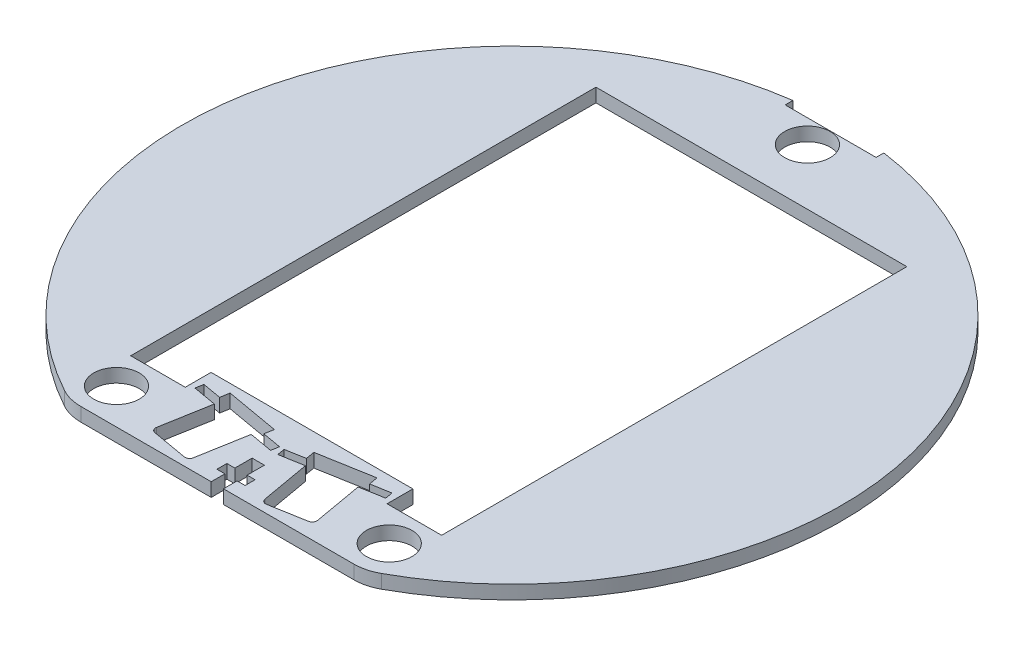
SolidWorks part; units mm, degrees
ref_plane "Front Plane" through (0, 0, 0) normal (0, 0, 1) x (1, 0, 0)
ref_plane "Top Plane" through (0, 0, 0) normal (0, 1, 0) x (1, 0, 0)
ref_plane "Right Plane" through (0, 0, 0) normal (1, 0, 0) x (0, 0, -1)
sketch "Sketch1" plane through (0, 0, 0) normal (0, 1, 0) x (1, 0, 0)
  line L0 (-30.03, -64.8129) -> (30.03, -64.8129)
  line L1 (0, -85) -> (0, 0) construction
  line L2 (0, -85) -> (32.4891, -64.8129) construction
  arc A0 (34.8348, -63.5829) -> (-34.8348, -63.5829) centre (0, 0) ccw
  circle A1 centre (0, -85) radius 38.25 construction
  arc A2 (30.03, -64.8129) -> (34.8348, -63.5829) centre (30.03, -54.8129) ccw
  arc A3 (-30.03, -64.8129) -> (-34.8348, -63.5829) centre (-30.03, -54.8129) cw
  dimension "D1" = 145
  dimension "D2" = 76.5
  dimension "D4" = 10
  dimension "D3" = 85
extrude "Boss-Extrude1" add sketch "Sketch1" along normal blind 3
sketch "Sketch2" plane through (0, 3, 0) normal (0, 1, 0) x (1, 0, 0)
  line L0 (-34.2, -49.6757) -> (-22.2, -49.6757)
  line L1 (-22.2, -49.6757) -> (-22.2, -44)
  line L2 (-22.2, 49.6757) -> (-22.2, 44)
  line L3 (0, 0) -> (0, -44) construction
  line L4 (34.2, 49.6757) -> (22.2, 49.6757)
  line L5 (34.2, -49.6757) -> (34.2, 49.6757)
  line L6 (22.2, 49.6757) -> (22.2, 44)
  line L7 (22.2, -49.6757) -> (22.2, -44)
  line L8 (34.2, -49.6757) -> (22.2, -49.6757)
  line L55 (-22.2, 44) -> (22.2, 44)
  line L63 (-34.2, -49.6757) -> (-34.2, 49.6757)
  line L64 (-34.2, 49.6757) -> (-22.2, 49.6757)
  line L77 (-22.2, -44) -> (22.2, -44)
  point P9 (0, 44)
  dimension "D1" = 44
  dimension "D2" = 44
  dimension "D3" = 34.2
  dimension "D4" = 12
  dimension "D5" = 49.6757
  dimension "D6" = 49.6757
extrude "Cut-Extrude1" cut sketch "Sketch2" against normal through all
sketch "Sketch4" plane through (0, 3, 0) normal (0, 1, 0) x (1, 0, 0)
  line L0 (-20.9838, -48.7531) -> (-0.7952, -52.3129)
  line L1 (20.9838, -48.7531) -> (20.6886, -47.0789)
  line L2 (0.7952, -52.3129) -> (0.5, -50.6387)
  line L3 (20.6886, -47.0789) -> (0.5, -50.6387)
  line L4 (0, 0) -> (0, -64.8129) construction
  line L5 (-30.03, -64.8129) -> (30.03, -64.8129) construction
  line L6 (-20.6886, -47.0789) -> (-0.5, -50.6387)
  line L7 (-0.7952, -52.3129) -> (-0.5, -50.6387)
  line L8 (-20.9838, -48.7531) -> (-20.6886, -47.0789)
  line L14 (20.9838, -48.7531) -> (0.7952, -52.3129)
  dimension "D1" = 1.7
  dimension "D2" = 20.5
  dimension "D3" = 10
  dimension "D4" = 12.5
  dimension "D5" = 0.5
extrude "Cut-Extrude3" cut sketch "Sketch4" against normal through all
sketch "Sketch5" plane through (0, 3, 0) normal (0, 1, 0) x (1, 0, 0)
  line L0 (5.9654, -51.4012) -> (15.8135, -49.6647)
  line L1 (5.9654, -51.4012) -> (7.8756, -62.2341)
  line L2 (15.8135, -49.6647) -> (17.7237, -60.4976)
  line L3 (9.034, -63.0453) -> (16.9125, -61.6561)
  line L4 (0.7952, -52.3129) -> (20.9838, -48.7531) construction
  line L5 (16.5031, -47.8169) -> (4.6854, -49.9007)
  line L6 (16.5031, -47.8169) -> (16.1558, -45.8473)
  line L7 (4.6854, -49.9007) -> (4.3381, -47.9311)
  line L8 (16.1558, -45.8473) -> (4.3381, -47.9311)
  line L9 (20.6886, -47.0789) -> (0.5, -50.6387) construction
  line L10 (0, -44) -> (0, -64.8129) construction
  line L12 (-30.03, -64.8129) -> (30.03, -64.8129) construction
  line L13 (-16.1558, -45.8473) -> (-4.3381, -47.9311)
  line L14 (-4.6854, -49.9007) -> (-4.3381, -47.9311)
  line L15 (-16.5031, -47.8169) -> (-16.1558, -45.8473)
  line L16 (-16.5031, -47.8169) -> (-4.6854, -49.9007)
  line L17 (-9.034, -63.0453) -> (-16.9125, -61.6561)
  line L18 (-15.8135, -49.6647) -> (-17.7237, -60.4976)
  line L19 (-5.9654, -51.4012) -> (-7.8756, -62.2341)
  line L20 (-5.9654, -51.4012) -> (-15.8135, -49.6647)
  line L21 (-22.2, -44) -> (22.2, -44) construction
  arc A0 (17.7237, -60.4976) -> (16.9125, -61.6561) centre (16.7388, -60.6713) cw
  arc A1 (7.8756, -62.2341) -> (9.034, -63.0453) centre (8.8604, -62.0605) ccw
  arc A2 (-7.8756, -62.2341) -> (-9.034, -63.0453) centre (-8.8604, -62.0605) cw
  arc A3 (-17.7237, -60.4976) -> (-16.9125, -61.6561) centre (-16.7388, -60.6713) ccw
  point P14 (10.5943, -48.8588)
  point P15 (10.5943, -48.8588)
  point P17 (10.8895, -50.533)
  point P18 (10.8895, -50.533)
  point P21 (17.8973, -61.4824)
  point P24 (8.0492, -63.2189)
  point P40 (-8.0492, -63.2189)
  point P41 (-17.8973, -61.4824)
  dimension "D5" = 1
  dimension "D1" = 12
  dimension "D2" = 10
  dimension "D3" = 12
  dimension "D4" = 2
extrude "Cut-Extrude4" cut sketch "Sketch5" against normal through all
sketch "Sketch6" plane through (0, 3, 0) normal (0, 1, 0) x (1, 0, 0)
  line L0 (34.2, 49.6757) -> (22.2, 49.6757) construction
  line L1 (34.2, -49.6757) -> (34.2, 49.6757) construction
  line L2 (-34.2, 49.6757) -> (34.2, 49.6757)
  line L3 (-34.2, 49.6757) -> (-34.2, 52.6757)
  line L4 (-34.2, 52.6757) -> (34.2, 52.6757)
  line L5 (34.2, 49.6757) -> (34.2, 52.6757)
  dimension "D1" = 3
extrude "Cut-Extrude5" cut sketch "Sketch6" against normal through all
sketch "Sketch7" plane through (0, 3, 0) normal (0, 1, 0) x (1, 0, 0)
  line L0 (0, 0) -> (0, -29.5093) construction
  circle A0 centre (-30, -57) radius 5
  circle A4 centre (30, -57) radius 5
  dimension "D1" = 10
  dimension "D2" = 57
  dimension "D3" = 30
extrude "Cut-Extrude6" cut sketch "Sketch7" against normal through all
sketch "Sketch8" plane through (0, 3, 0) normal (0, 1, 0) x (1, 0, 0)
  line L10 (-52.7, 37.2865) -> (-52.7, 32.5)
  line L11 (-52.7, 32.5) -> (-43.3, 32.5)
  line L12 (-43.3, 32.5) -> (-43.3, 37.2865)
  line L13 (-43.3, 37.2865) -> (-43.3, 42.7135)
  line L14 (-43.3, 42.7135) -> (-48, 45.4271)
  line L15 (-48, 45.4271) -> (-52.7, 42.7135)
  line L16 (-52.7, 42.7135) -> (-52.7, 37.2865)
  line L17 (-52.7, 37.2865) -> (-52.7, 32.5)
  line L18 (-52.7, 32.5) -> (-43.3, 32.5)
  line L19 (-43.3, 32.5) -> (-43.3, 37.2865)
  line L20 (-43.3, 37.2865) -> (-43.3, 42.7135)
  line L21 (-43.3, 42.7135) -> (-48, 45.4271)
  line L22 (-48, 45.4271) -> (-52.7, 42.7135)
  line L23 (-52.7, 42.7135) -> (-52.7, 37.2865)
  line L24 (44.7, -32.5) -> (35.3, -32.5)
  line L25 (44.7, -37.2865) -> (44.7, -32.5)
  line L26 (44.7, -42.7135) -> (44.7, -37.2865)
  line L31 (40, -45.4271) -> (44.7, -42.7135)
  line L32 (35.3, -42.7135) -> (40, -45.4271)
  line L33 (35.3, -37.2865) -> (35.3, -42.7135)
  line L34 (35.3, -32.5) -> (35.3, -37.2865)
  line L35 (44.7, -32.5) -> (35.3, -32.5)
  line L36 (44.7, -37.2865) -> (44.7, -32.5)
  line L37 (44.7, -42.7135) -> (44.7, -37.2865)
  line L38 (40, -45.4271) -> (44.7, -42.7135)
  line L39 (35.3, -42.7135) -> (40, -45.4271)
  line L40 (35.3, -37.2865) -> (35.3, -42.7135)
  line L41 (35.3, -32.5) -> (35.3, -37.2865)
  line L42 (-35.3, -37.2865) -> (-35.3, -32.5)
  line L43 (-35.3, -32.5) -> (-44.7, -32.5)
  line L44 (-44.7, -32.5) -> (-44.7, -37.2865)
  line L45 (-44.7, -37.2865) -> (-44.7, -42.7135)
  line L46 (-44.7, -42.7135) -> (-40, -45.4271)
  line L47 (-40, -45.4271) -> (-35.3, -42.7135)
  line L48 (-35.3, -42.7135) -> (-35.3, -37.2865)
  line L49 (-35.3, -37.2865) -> (-35.3, -32.5)
  line L50 (-35.3, -32.5) -> (-44.7, -32.5)
  line L51 (-44.7, -32.5) -> (-44.7, -37.2865)
  line L52 (-44.7, -37.2865) -> (-44.7, -42.7135)
  line L53 (-44.7, -42.7135) -> (-40, -45.4271)
  line L54 (-40, -45.4271) -> (-35.3, -42.7135)
  line L55 (-35.3, -42.7135) -> (-35.3, -37.2865)
  line L56 (52.7, 32.5) -> (52.7, 37.2865)
  line L57 (52.7, 37.2865) -> (52.7, 42.7135)
  line L58 (52.7, 42.7135) -> (48, 45.4271)
  line L59 (48, 45.4271) -> (43.3, 42.7135)
  line L60 (43.3, 42.7135) -> (43.3, 37.2865)
  line L61 (43.3, 37.2865) -> (43.3, 32.5)
  line L62 (43.3, 32.5) -> (52.7, 32.5)
  line L63 (52.7, 32.5) -> (52.7, 37.2865)
  line L64 (52.7, 37.2865) -> (52.7, 42.7135)
  line L65 (52.7, 42.7135) -> (48, 45.4271)
  line L66 (48, 45.4271) -> (43.3, 42.7135)
  line L67 (43.3, 42.7135) -> (43.3, 37.2865)
  line L68 (43.3, 37.2865) -> (43.3, 32.5)
  line L69 (43.3, 32.5) -> (52.7, 32.5)
  dimension "D1" = 0
  dimension "D2" = 0
  dimension "D3" = 0
  dimension "D4" = 0
extrude "Cut-Extrude7" [suppressed] cut sketch "Sketch8" against normal through all
sketch "Sketch11" plane through (0, 3, 0) normal (0, 1, 0) x (1, 0, 0)
  line L0 (0, 0) -> (0, 65) construction
  circle A0 centre (0, 65) radius 5
  dimension "D2" = 10
  dimension "D1" = 65
extrude "Cut-Extrude10" cut sketch "Sketch11" against normal through all
sketch "Sketch12" plane through (0, 3, 0) normal (0, 1, 0) x (1, 0, 0)
  line L0 (-30.03, -64.8129) -> (30.03, -64.8129) construction
  line L1 (-1.35, -64.8129) -> (1.35, -64.8129)
  line L2 (-1.35, -64.8129) -> (-1.35, -61.8129)
  line L3 (-1.35, -55.8129) -> (1.35, -55.8129)
  line L4 (1.35, -64.8129) -> (1.35, -61.8129)
  line L5 (-1.35, -59.6129) -> (-3.1, -59.6129)
  line L6 (3.1, -59.6129) -> (1.35, -59.6129)
  line L7 (3.1, -59.6129) -> (3.1, -61.8129)
  line L8 (3.1, -61.8129) -> (1.35, -61.8129)
  line L9 (-3.1, -59.6129) -> (-3.1, -61.8129)
  line L10 (-1.35, -61.8129) -> (-3.1, -61.8129)
  line L11 (-1.35, -59.6129) -> (-1.35, -55.8129)
  line L12 (1.35, -59.6129) -> (1.35, -55.8129)
  point P14 (0, -64.8129)
  point P15 (0, -64.8129)
  dimension "D1" = 3
  dimension "D2" = 9
  dimension "D3" = 2.7
  dimension "D4" = 2.2
  dimension "D5" = 6.2
extrude "Cut-Extrude11" [suppressed] cut sketch "Sketch12" against normal through all
sketch "Sketch13" plane through (0, 3, 0) normal (0, 1, 0) x (1, 0, 0)
  line L0 (0, 0) -> (0, -22.8942) construction
  circle A0 centre (45, -48) radius 1.65
  circle A1 centre (-45, -48) radius 1.65
  circle A2 centre (40, 50) radius 1.65
  circle A3 centre (-40, 50) radius 1.65
  dimension "D3" = 3.3
  dimension "D1" = 48
  dimension "D2" = 45
  dimension "D4" = 40
  dimension "D5" = 50
extrude "Cut-Extrude12" [suppressed] cut sketch "Sketch13" against normal through all
sketch "Sketch14" plane through (0, 0, 0) normal (0, -1, 0) x (1, 0, 0)
  line L8 (-41.543, 56.9759) -> (-42.0754, 56.6031)
  line L9 (-42.0754, 56.6031) -> (-40.0679, 53.736)
  line L10 (-40.0679, 53.736) -> (-36.7913, 56.0303)
  line L11 (-36.7913, 56.0303) -> (-38.7988, 58.8974)
  line L12 (-38.7988, 58.8974) -> (-39.3313, 58.5245)
  line L13 (-39.3313, 58.5245) -> (-40.4784, 60.1629)
  line L14 (-40.4784, 60.1629) -> (-42.6901, 58.6142)
  line L15 (-42.6901, 58.6142) -> (-41.543, 56.9759)
  line L16 (-41.543, 56.9759) -> (-42.0754, 56.6031)
  line L17 (-42.0754, 56.6031) -> (-40.0679, 53.736)
  line L18 (-40.0679, 53.736) -> (-36.7913, 56.0303)
  line L19 (-36.7913, 56.0303) -> (-38.7988, 58.8974)
  line L20 (-38.7988, 58.8974) -> (-39.3313, 58.5245)
  line L21 (-39.3313, 58.5245) -> (-40.4784, 60.1629)
  line L22 (-40.4784, 60.1629) -> (-42.6901, 58.6142)
  line L23 (-42.6901, 58.6142) -> (-41.543, 56.9759)
  line L24 (41.543, 56.9759) -> (42.6901, 58.6142)
  line L25 (42.0754, 56.6031) -> (41.543, 56.9759)
  line L26 (40.0679, 53.736) -> (42.0754, 56.6031)
  line L27 (36.7913, 56.0303) -> (40.0679, 53.736)
  line L28 (38.7988, 58.8974) -> (36.7913, 56.0303)
  line L29 (39.3313, 58.5245) -> (38.7988, 58.8974)
  line L30 (40.4784, 60.1629) -> (39.3313, 58.5245)
  line L31 (42.6901, 58.6142) -> (40.4784, 60.1629)
  line L32 (41.543, 56.9759) -> (42.6901, 58.6142)
  line L33 (42.0754, 56.6031) -> (41.543, 56.9759)
  line L34 (40.0679, 53.736) -> (42.0754, 56.6031)
  line L35 (36.7913, 56.0303) -> (40.0679, 53.736)
  line L36 (38.7988, 58.8974) -> (36.7913, 56.0303)
  line L37 (39.3313, 58.5245) -> (38.7988, 58.8974)
  line L38 (40.4784, 60.1629) -> (39.3313, 58.5245)
  line L39 (42.6901, 58.6142) -> (40.4784, 60.1629)
  dimension "D1" = 0
  dimension "D2" = 0
extrude "Cut-Extrude13" [suppressed] cut sketch "Sketch14" against normal through all
sketch "Sketch15" plane through (0, 3, 0) normal (0, 1, 0) x (1, 0, 0)
  line L1 (10, 71.807) -> (-10, 71.807)
  line L2 (10, 71.807) -> (10, 70.107)
  line L3 (10, 70.107) -> (-10, 70.107)
  line L4 (-10, 71.807) -> (-10, 70.107)
  arc A0 (34.8348, -63.5829) -> (-34.8348, -63.5829) centre (0, 0) ccw construction
  dimension "D1" = 20
  dimension "D2" = 1.7
extrude "Cut-Extrude14" cut sketch "Sketch15" against normal through all
sketch "Sketch16" plane through (0, 3, 0) normal (0, 1, 0) x (1, 0, 0)
  line L0 (-30.03, -64.8129) -> (30.03, -64.8129) construction
  line L1 (-1.35, -64.8129) -> (1.35, -64.8129)
  line L2 (-1.35, -64.8129) -> (-1.35, -61.8129)
  line L3 (-1.35, -55.8129) -> (1.35, -55.8129)
  line L4 (1.35, -64.8129) -> (1.35, -61.8129)
  line L5 (-1.35, -59.6129) -> (-3.1, -59.6129)
  line L6 (3.1, -59.6129) -> (1.35, -59.6129)
  line L7 (3.1, -59.6129) -> (3.1, -61.8129)
  line L8 (3.1, -61.8129) -> (1.35, -61.8129)
  line L9 (-3.1, -59.6129) -> (-3.1, -61.8129)
  line L10 (-1.35, -61.8129) -> (-3.1, -61.8129)
  line L11 (-1.35, -59.6129) -> (-1.35, -55.8129)
  line L12 (1.35, -59.6129) -> (1.35, -55.8129)
  point P10 (0, -64.8129)
  point P11 (0, -64.8129)
  dimension "D1" = 2.7
  dimension "D2" = 2.2
  dimension "D3" = 6.2
  dimension "D4" = 3
  dimension "D5" = 9
extrude "Cut-Extrude15" cut sketch "Sketch16" against normal through all
equation "\"smallPulleyTeeth\"= 30"
equation "\"largePulleyTeeth\"= 30"
equation "\"eighthThick\"= 3.0mm"
equation "\"sixteenthThick\" = 1.7mm"
equation "\"quarterThick\"=6.0mm"
equation "\"OD\" = 145mm"
equation "\"puckAngle\" = 60.5deg"
equation "\"puckDiam\" = 76.5mm"
equation "\"axlePress\" = 5.9mm"
equation "\"press\" = 0.2mm"
equation "\"wheelClear\" = 0.3mm"
equation "\"10-32clear\" = 4.8mm"
equation "\"6-32clear\" = 3.3mm"
equation "\"8-32clear\" = 4.0mm"
equation "\"4-40clear\" = 3.0mm"
equation "\"wheelHeight\" = 22mm"
equation "\"wheelWell\" = 65mm"
equation "\"D1@Sketch1\"=\"OD\""
equation "\"D1@Boss-Extrude1\"=\"eighthThick\""
equation "\"D2@Sketch1\"=\"puckDiam\""
equation "\"puckDist\" = 85mm"
equation "\"scoopFillet\" = 5mm"
equation "\"10-32tap\" = 4.45mm"
equation "\"ledSmall\" = 3.1mm"
equation "\"ledLarge\" = 4.2mm"
equation "\"ledLength\" = 4.2mm"
equation "\"D3@Sketch1\"=\"puckDist\""
equation "\"4-40close\" = 2.7mm"
equation "\"4-40nutThick\" = 2.2mm"
equation "\"4-40nutWidth\" = 6.2mm"
equation "\"D3@Sketch12\"=\"4-40close\""
equation "\"D4@Sketch12\"=\"4-40nutThick\""
equation "\"D5@Sketch12\"=\"4-40nutWidth\""
equation "\"D3@Sketch13\"=\"6-32clear\""
equation "\"D1@Sketch6\"=\"eighthThick\""
equation "\"D2@Sketch15\"=\"sixteenthThick\""
equation "\"D1@Sketch16\"=\"4-40close\""
equation "\"D2@Sketch16\"=\"4-40nutThick\""
equation "\"D3@Sketch16\"=\"4-40nutWidth\""
